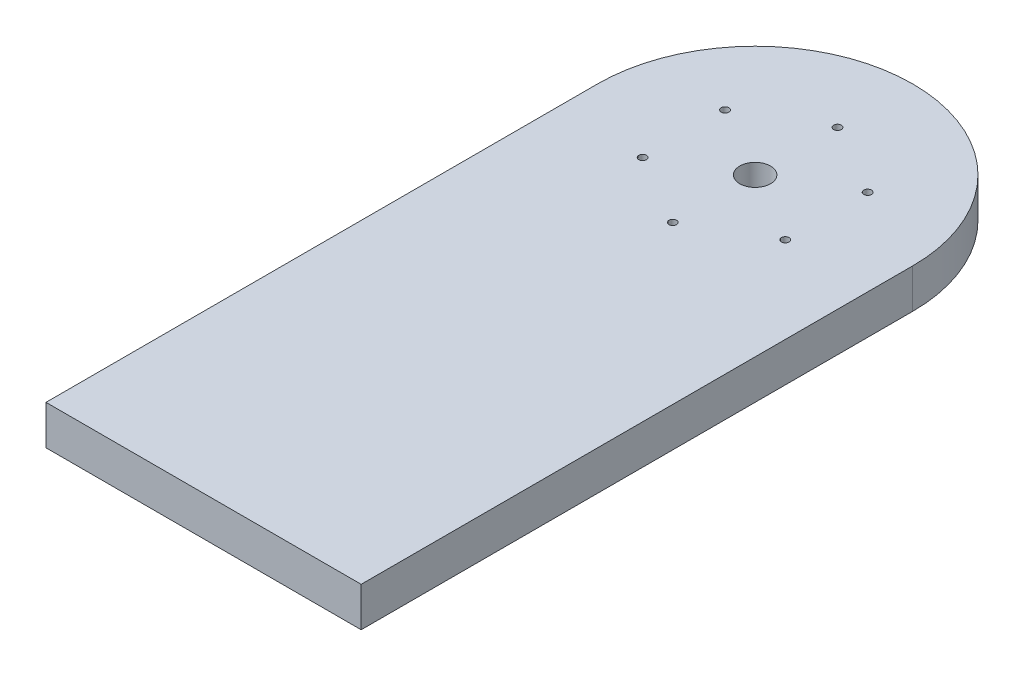
SolidWorks part; units mm, degrees
ref_plane "Front Plane" through (0, 0, 0) normal (0, 0, 1) x (1, 0, 0)
ref_plane "Top Plane" through (0, 0, 0) normal (0, 1, 0) x (1, 0, 0)
ref_plane "Right Plane" through (0, 0, 0) normal (1, 0, 0) x (0, 0, -1)
sketch "Sketch1" plane through (0, 0, 0) normal (0, 1, 0) x (1, 0, 0)
  line L1 (-25.4, 0) -> (-25.4, -88.9)
  line L2 (25.4, 0) -> (25.4, -88.9)
  line L3 (-25.4, -88.9) -> (25.4, -88.9)
  arc A0 (25.4, 0) -> (-25.4, 0) centre (0, 0) ccw
  dimension "D1" = 88.9
  dimension "D2" = 25.4
  dimension "D3" = 50.8
extrude "Boss-Extrude1" add sketch "Sketch1" along normal blind 6.35
sketch "Sketch2" plane through (0, 6.35, 0) normal (0, 1, 0) x (1, 0, 0)
  circle A0 centre (0, 13.271) radius 0.62
  circle A1 centre (0, -13.271) radius 0.62
  circle A2 centre (-11.493, 6.6355) radius 0.62
  circle A3 centre (-11.493, -6.6355) radius 0.62
  circle A4 centre (11.493, 6.6355) radius 0.62
  circle A5 centre (11.493, -6.6355) radius 0.62
  dimension "D1" = 26.542
  dimension "D3" = 26.542
  dimension "D2" = 13.271
  dimension "D4" = 13.271
  dimension "D5" = 26.542
  dimension "D6" = 13.271
  dimension "D7" = 13.271
  dimension "D8" = 13.271
  dimension "D9" = 13.271
  dimension "D10" = 13.271
extrude "Cut-Extrude1" cut sketch "Sketch2" against normal blind 6.35
sketch "Sketch3" plane through (0, 6.35, 0) normal (0, 1, 0) x (1, 0, 0)
  circle A0 centre (0, 0) radius 2.4801
extrude "Cut-Extrude2" cut sketch "Sketch3" against normal blind 6.35
